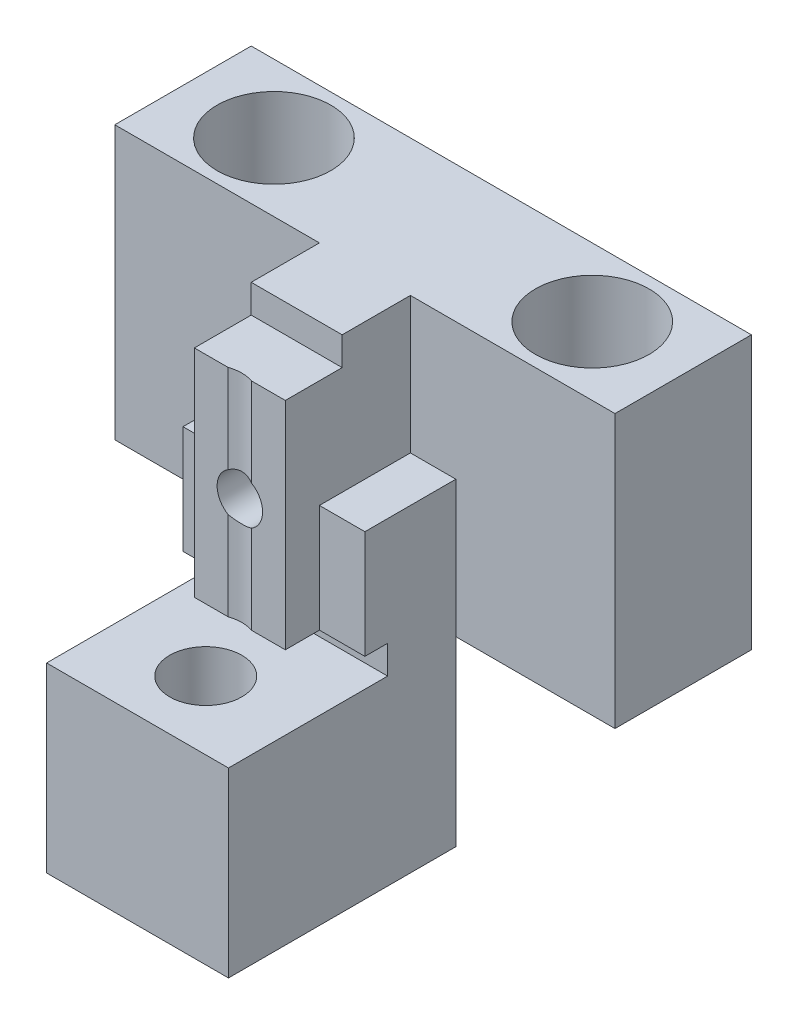
SolidWorks part; units mm, degrees
material "7075-T6 (SN)"
ref_plane "Front Plane" through (0, 0, 0) normal (0, 0, 1) x (1, 0, 0)
ref_plane "Top Plane" through (0, 0, 0) normal (0, 1, 0) x (1, 0, 0)
ref_plane "Right Plane" through (0, 0, 0) normal (1, 0, 0) x (0, 0, -1)
sketch "Sketch1" plane through (0, 0, 0) normal (0, 0, 1) x (1, 0, 0)
  line L1 (-22, -12) -> (22, -12)
  line L2 (-22, -12) -> (-22, 12)
  line L3 (-22, 12) -> (22, 12)
  line L4 (22, -12) -> (22, 12)
extrude "Crosshead_Base" add sketch "Sketch1" along normal blind 12
sketch "Sketch2" plane through (0, 0, 0) normal (0, 0, 1) x (1, 0, 0)
  line L1 (-4, -12) -> (4, -12)
  line L2 (-4, -12) -> (-4, 12)
  line L3 (-4, 12) -> (4, 12)
  line L4 (4, -12) -> (4, 12)
extrude "Shoe_Upriser" add sketch "Sketch2" along normal blind 11 from offset 12
sketch "Sketch3" plane through (0, 0, 0) normal (0, 0, 1) x (1, 0, 0)
  line L1 (-8, -28) -> (8, -28)
  line L2 (-8, -28) -> (-8, 0)
  line L3 (-8, 0) -> (8, 0)
  line L4 (8, -28) -> (8, 0)
extrude "Adapter_Bridge" add sketch "Sketch3" along normal blind 8 from offset 12
sketch "Sketch4" plane through (0, 0, 0) normal (0, 0, 1) x (1, 0, 0)
  line L1 (-8, -28) -> (8, -28)
  line L2 (-8, -28) -> (-8, -12)
  line L3 (-8, -12) -> (8, -12)
  line L4 (8, -28) -> (8, -12)
extrude "Threaded_Rod_Adapter" add sketch "Sketch4" along normal blind 12 from offset 20
sketch "Sketch5" plane through (0, 0, 0) normal (0, 1, 0) x (1, 0, 0)
  circle A0 centre (-14, -6) radius 5
  circle A1 centre (14, -6) radius 5
extrude "Two_Bronze_Bush_Housings" cut sketch "Sketch5" against normal through all and the other way through all
sketch "Sketch6" plane through (0, 0, 0) normal (0, 1, 0) x (1, 0, 0)
  circle A0 centre (0, -26) radius 3.175
extrude "Quarter20_Adapter_Major_Envelope" cut sketch "Sketch6" against normal through all and the other way through all
sketch "Sketch7" plane through (0, 0, 23) normal (0, 0, 1) x (1, 0, 0)
  circle A0 centre (0, 0) radius 2
extrude "M4_Shoe_Thread_Major_Envelope" cut sketch "Sketch7" against normal blind 11
sketch "Sketch8" plane through (0, 0, 0) normal (1, 0, 0) x (0, 0, -1)
  line L0 (-18, -12) -> (-18, -9.5)
  line L1 (-18, -9.5) -> (-23.5, -9.5)
  line L2 (-23.5, -9.5) -> (-23.5, -12)
  line L3 (-23.5, -12) -> (-18, -12)
  line L4 (-18, 9.5) -> (-18, 12.5)
  line L5 (-18, 12.5) -> (-23.5, 12.5)
  line L6 (-23.5, 12.5) -> (-23.5, 9.5)
  line L7 (-23.5, 9.5) -> (-18, 9.5)
extrude "Cross_Slot_Bottom_Clearance" cut sketch "Sketch8" against normal through all and the other way through all
